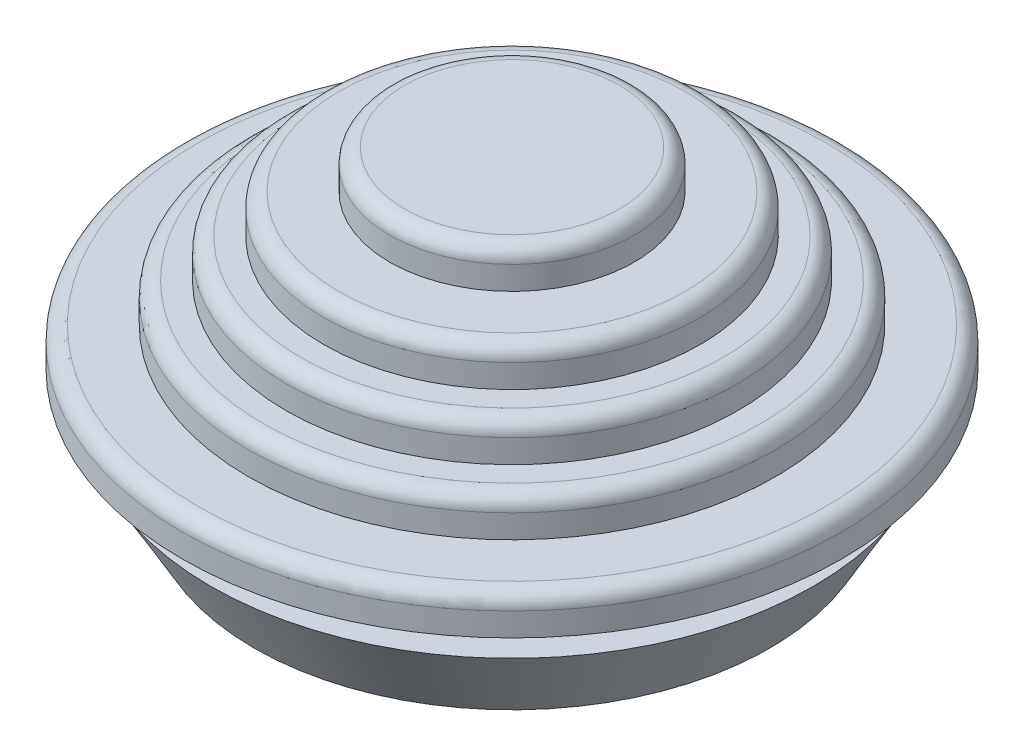
SolidWorks part; units mm, degrees
material "PBT General Purpose"
ref_plane "Front Plane" through (0, 0, 0) normal (0, 0, 1) x (1, 0, 0)
ref_plane "Top Plane" through (0, 0, 0) normal (0, 1, 0) x (1, 0, 0)
ref_plane "Right Plane" through (0, 0, 0) normal (1, 0, 0) x (0, 0, -1)
sketch "Sketch1" plane through (0, 0, 0) normal (0, 0, 1) x (1, 0, 0)
  line L0 (0, 67.947) -> (0, 0) construction
  line L1 (12.4, 0) -> (13.6906, 0)
  line L2 (13.6906, 0) -> (16, 4)
  line L3 (16, 4) -> (14.5, 4)
  line L4 (14.5, 4) -> (14.5, 6)
  line L5 (14.5, 6) -> (17.5, 6)
  line L6 (17.5, 6) -> (17.5, 8.04)
  line L7 (17.5, 8.04) -> (14, 8.04)
  line L8 (14, 8.04) -> (14, 10.08)
  line L9 (14, 10.08) -> (12, 10.08)
  line L10 (12, 10.08) -> (12, 12.12)
  line L11 (12, 12.12) -> (10, 12.12)
  line L12 (10, 12.12) -> (10, 14.16)
  line L13 (10, 14.16) -> (6.5, 14.16)
  line L14 (6.5, 14.16) -> (6.5, 16.2)
  line L15 (6.5, 16.2) -> (0, 16.2)
  line L16 (12.4, 0) -> (12.4, 8.08)
  line L17 (-17.5, 6) -> (-17.5, 8.04) construction
  line L18 (-12.4, 0) -> (-12.4, 8.08) construction
  line L19 (-6.5, 14.16) -> (-6.5, 16.2) construction
  line L20 (-10, 14.16) -> (-6.5, 14.16) construction
  line L21 (-10, 12.12) -> (-10, 14.16) construction
  line L22 (-12, 12.12) -> (-10, 12.12) construction
  line L23 (-12, 10.08) -> (-12, 12.12) construction
  line L24 (-14, 10.08) -> (-12, 10.08) construction
  line L25 (-14, 8.04) -> (-14, 10.08) construction
  line L26 (-17.5, 8.04) -> (-14, 8.04) construction
  line L27 (-14.5, 6) -> (-17.5, 6) construction
  line L28 (-14.5, 4) -> (-14.5, 6) construction
  line L29 (-16, 4) -> (-14.5, 4) construction
  line L30 (-13.6906, 0) -> (-16, 4) construction
  line L31 (-12.4, 0) -> (-13.6906, 0) construction
  line L32 (0, 16.2) -> (0, 12.16)
  line L33 (10, 8.08) -> (12.4, 8.08)
  line L34 (10, 8.08) -> (10, 10.12)
  line L35 (10, 10.12) -> (8, 10.12)
  line L36 (8, 10.12) -> (8, 12.16)
  line L37 (8, 12.16) -> (0, 12.16)
  line L38 (14, 8.08) -> (10, 8.08) construction
  line L39 (8, 12.16) -> (6.5, 12.16) construction
  dimension "D1" = 24.8
  dimension "D2" = 2
  dimension "D3" = 4
  dimension "D4" = 60
  dimension "D5" = 29
  dimension "D6" = 13
  dimension "D7" = 20
  dimension "D8" = 24
  dimension "D9" = 28
  dimension "D10" = 35
  dimension "D11" = 16.2
  dimension "D12" = 2
  dimension "D13" = 32
revolve "Revolve1" add sketch "Sketch1" angle 360 about L0
fillet "Fillet1" radius 0.8 5 edges at (0, 16.2, 6.5) (0, 14.16, 10) (0, 12.12, 12) (0, 10.08, 14) (0, 8.04, 17.5)
